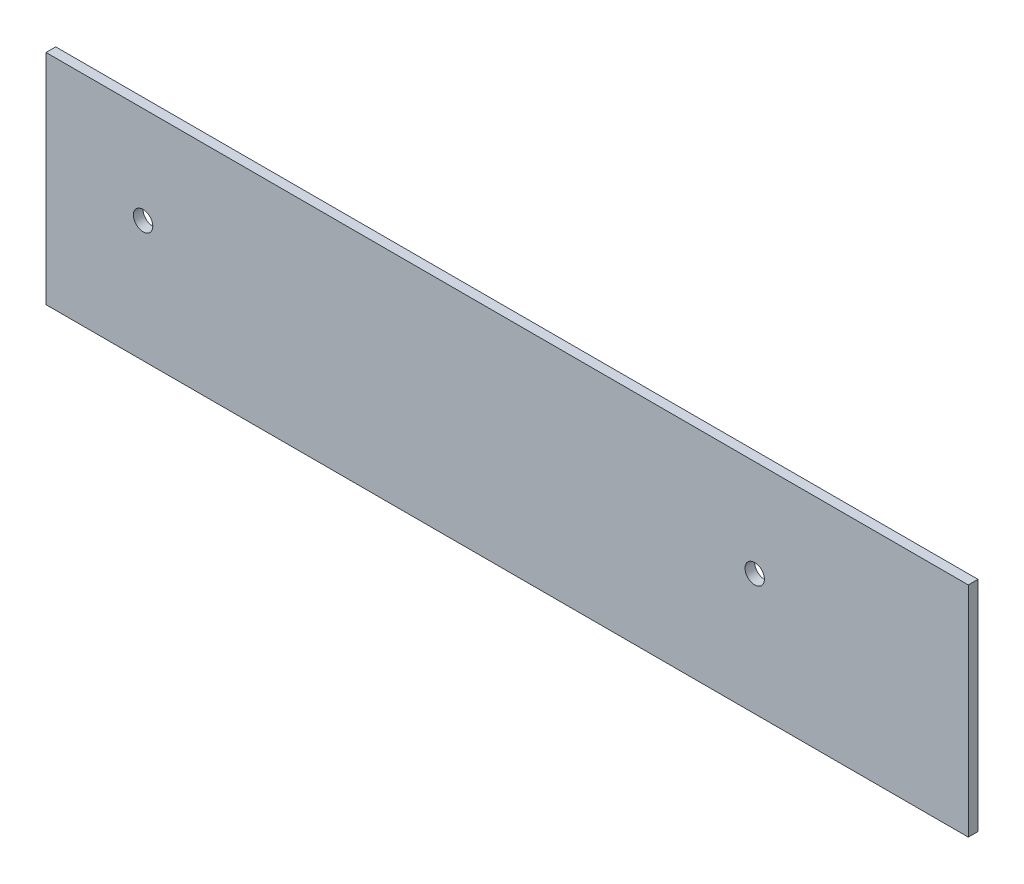
SolidWorks part; units mm, degrees
ref_plane "Front Plane" through (0, 0, 0) normal (0, 0, 1) x (1, 0, 0)
ref_plane "Top Plane" through (0, 0, 0) normal (0, 1, 0) x (1, 0, 0)
ref_plane "Right Plane" through (0, 0, 0) normal (1, 0, 0) x (0, 0, -1)
sketch "Sketch2" plane through (0, 0, 0) normal (0, 0, 1) x (1, 0, 0)
  line L1 (-95, 22.5) -> (95, 22.5)
  line L2 (-95, 22.5) -> (-95, -22.5)
  line L3 (-95, -22.5) -> (95, -22.5)
  line L4 (95, 22.5) -> (95, -22.5)
  line L5 (-95, 22.5) -> (95, -22.5) construction
  line L6 (-95, -22.5) -> (95, 22.5) construction
  point P0 (0, 0)
  dimension "D1" = 45
  dimension "D2" = 190
extrude "Boss-Extrude1" add sketch "Sketch2" along normal blind 2
sketch "Sketch3" plane through (0, 0, 2) normal (0, 0, 1) x (1, 0, 0)
  line L0 (-95, -22.5) -> (95, -22.5) construction
  line L1 (-95, 22.5) -> (-95, -22.5) construction
  circle A0 centre (-75, 2.5) radius 2
  circle A1 centre (51, 2.5) radius 2
  dimension "D1" = 4
  dimension "D2" = 4
  dimension "D3" = 25
  dimension "D4" = 25
  dimension "D5" = 146
  dimension "D6" = 20
extrude "Cut-Extrude1" cut sketch "Sketch3" against normal blind 2
